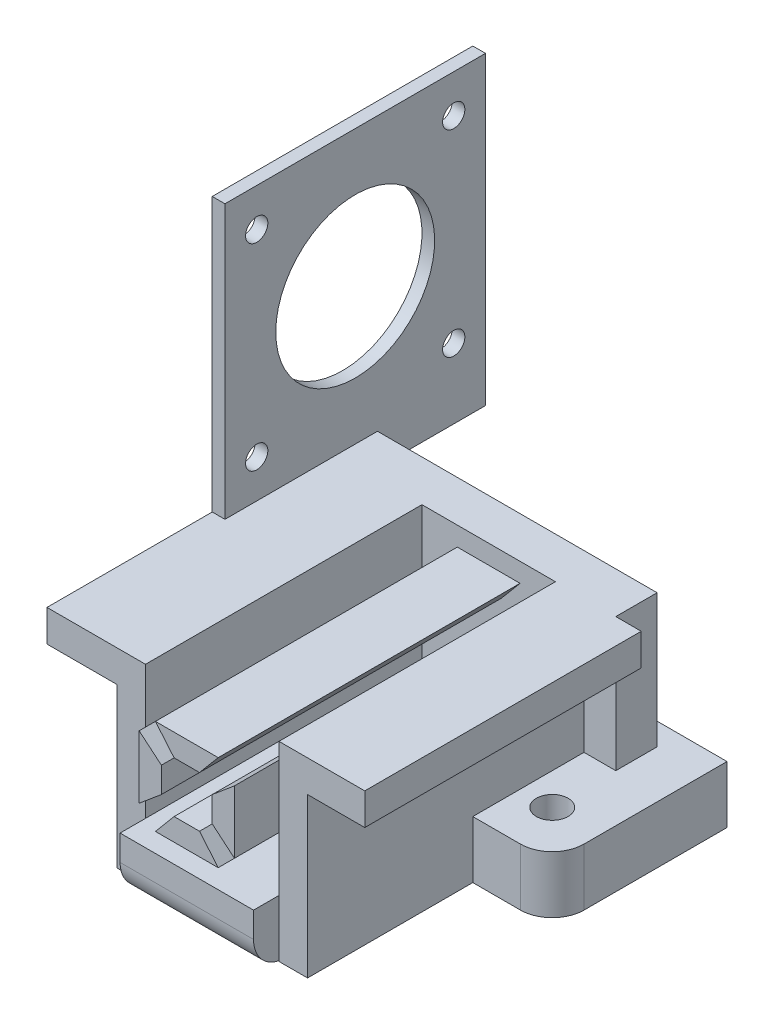
SolidWorks part; units mm, degrees
ref_plane "Front Plane" through (0, 0, 0) normal (0, 0, 1) x (1, 0, 0)
ref_plane "Top Plane" through (0, 0, 0) normal (0, 1, 0) x (1, 0, 0)
ref_plane "Right Plane" through (0, 0, 0) normal (1, 0, 0) x (0, 0, -1)
sketch "Sketch1" plane through (0, 0, 0) normal (0, 1, 0) x (1, 0, 0)
  line L0 (27.5, 55) -> (27.5, 0) construction
  line L1 (5, 0) -> (50, 0)
  line L2 (0, 5) -> (0, 50)
  line L3 (5, 55) -> (50, 55)
  line L4 (55, 5) -> (55, 50)
  line L5 (0, 55) -> (7.5, 55) construction
  line L6 (0, 55) -> (0, 47.5) construction
  line L7 (0, 47.5) -> (7.5, 47.5) construction
  line L8 (7.5, 55) -> (7.5, 47.5) construction
  line L9 (0, 27.5) -> (55, 27.5) construction
  circle A0 centre (7.5, 47.5) radius 2.5
  circle A1 centre (47.5, 47.5) radius 2.5
  circle A2 centre (47.5, 7.5) radius 2.5
  circle A3 centre (7.5, 7.5) radius 2.5
  arc A4 (50, 0) -> (55, 5) centre (50, 5) ccw
  arc A5 (50, 55) -> (55, 50) centre (50, 50) cw
  arc A6 (0, 50) -> (5, 55) centre (5, 50) cw
  arc A7 (5, 0) -> (0, 5) centre (5, 5) cw
  point P23 (55, 55)
  point P29 (0, 0)
  dimension "D3" = 2
  dimension "D5" = 5
  dimension "D1" = 55
  dimension "D2" = 55
  dimension "D4" = 2
extrude "Boss-Extrude2" add sketch "Sketch1" along normal blind 8 and the other way blind 1
sketch "Sketch2" plane through (0, 8, 0) normal (0, 1, 0) x (1, 0, 0)
  line L0 (0, 27.5) -> (55, 27.5)
  line L1 (0, 50) -> (0, 5) construction
  line L2 (55, 5) -> (55, 50) construction
  line L4 (0, 27.5) -> (55, 27.5)
  line L5 (0, 27.5) -> (0, 55)
  line L6 (0, 55) -> (55, 55)
  line L7 (55, 27.5) -> (55, 55)
  circle M3 centre (7.5, 47.5) radius 2.5
  line M5 (55, 5) -> (55, 50)
  arc M6 (55, 50) -> (50, 55) centre (50, 50) ccw
  line M7 (50, 55) -> (5, 55)
  arc M8 (5, 55) -> (0, 50) centre (5, 50) ccw
  line M9 (0, 50) -> (0, 5)
  circle M12 centre (47.5, 47.5) radius 2.5
  dimension "D1" = 27.5
extrude "Cut-Extrude1" cut sketch "Sketch2" against normal through all both and the other way through all contours L0 M9 M5 M6 M7 M8 M12 M3
sketch "Sketch3" plane through (0, 0, -27.5) normal (0, 0, -1) x (-1, 0, 0)
  line L0 (0, -1) -> (0, 8) construction
  line L1 (-55, -1) -> (-37.5, -1) construction
  line L2 (-55, -1) -> (-55, 3.5) construction
  line L3 (-55, 3.5) -> (-37.5, 3.5) construction
  line L4 (-37.5, -1) -> (-37.5, 3.5) construction
  line L5 (0, -1) -> (-55, -1) construction
  circle A0 centre (-37.5, 3.5) radius 3.25
  circle A1 centre (-17.5, 3.5) radius 3.25
  point P10 (0, 3.5)
  dimension "D3" = 6.5
  dimension "D4" = 2
  dimension "D5" = 17.5
  dimension "D1" = 4.5
  dimension "D2" = 17.5
  dimension "D6" = 4.5
sketch3d "3DSketch1"
  point P0 (9.6264, 4.1069, -27.5)
sketch "Sketch5" plane through (0, 8, 0) normal (0, 1, 0) x (1, 0, 0)
  line L0 (27.5, 27.5) -> (27.5, 0)
  line L1 (0, 27.5) -> (55, 27.5) construction
  line L2 (5, 0) -> (50, 0) construction
  line L3 (27.5, 27.5) -> (27.5, 24)
  line L5 (27.5, 24) -> (23, 24)
  line L6 (27.5, 24) -> (27.5, 17.5)
  line L7 (27.5, 17.5) -> (23, 17.5)
  line L8 (23, 24) -> (23, 17.5)
  line L9 (27.5, 24) -> (32, 24)
  line L10 (27.5, 24) -> (27.5, 17.5)
  line L11 (27.5, 17.5) -> (32, 17.5)
  line L12 (32, 24) -> (32, 17.5)
  dimension "D1" = 3.5
  dimension "D2" = 6.5
  dimension "D3" = 4.5
  dimension "D4" = 4.5
  dimension "D5" = 6.5
extrude "Cut-Extrude5" cut sketch "Sketch3" against normal blind 15 draft 0.057 contours A0 | A1
extrude "Boss-Extrude3" add sketch "Sketch5" along normal blind 14.5 contours L5 L8 L7 L0 | L12 L9 L0 L11
sketch "Sketch6" plane through (0, 0, -24) normal (0, 0, -1) x (-1, 0, 0)
  line L0 (-27.5, 8) -> (-27.5, 17)
  line L1 (-32, 8) -> (-23, 8) construction
  circle A0 centre (-27.5, 17) radius 4
  dimension "D2" = 8
  dimension "D1" = 9
extrude "Cut-Extrude4" cut sketch "Sketch6" against normal blind 1.5
sketch "Sketch11" plane through (0, 0, -24) normal (0, 0, -1) x (-1, 0, 0)
  line L0 (-27.5, 22.5) -> (-25.5, 22.5)
  line L1 (-32.4368, 26) -> (-22.5632, 26)
  line L2 (-32, 22.5) -> (-23, 22.5) construction
  line L3 (-25.5, 22.5) -> (-27.5, 22.5)
  line L4 (-25.5, 22.5) -> (-29.5, 22.5)
  line L5 (-25.5, 22.5) -> (-25.5, 26)
  line L6 (-25.5, 26) -> (-29.5, 26)
  line L7 (-29.5, 22.5) -> (-29.5, 26)
  line L8 (-22.5632, 26) -> (-25.5, 22.5)
  line L9 (-29.5, 22.5) -> (-32.4368, 26)
  point P10 (-27.5, 26)
  line M9 (-23, 22.5) -> (-32, 22.5)
  dimension "D1" = 2
  dimension "D2" = 4
  dimension "D3" = 3.5
  dimension "D4" = 40
sketch "Sketch12" plane through (0, 8, 0) normal (0, 1, 0) x (1, 0, 0)
  line L0 (27.5, 17.5) -> (27.5, 0)
  line L1 (32, 17.5) -> (23, 17.5) construction
  line L2 (5, 0) -> (50, 0) construction
  line L3 (17, 0) -> (17, -30)
  line L4 (17, 0) -> (38, 0)
  line L5 (27.5, 0) -> (27.5, -30)
  line L6 (17, -30) -> (38, -30)
  line L7 (38, 0) -> (38, -30)
  point P9 (23.9675, 0)
  line M9 (5, 0) -> (50, 0)
  dimension "D1" = 30
  dimension "D2" = 10.5
extrude "Boss-Extrude7" add sketch "Sketch12" against normal blind 9 contours L7 L5 L6 M9 | L3 L6 L5 M9
sketch "Sketch15" plane through (0, 22.5, 0) normal (0, 1, 0) x (1, 0, 0)
  line L0 (32, 24) -> (32, 17.5) construction
  line L1 (32, 17.5) -> (23, 17.5)
  line L2 (32, 17.5) -> (32, 24)
  line L3 (32, 24) -> (23, 24)
  line L4 (23, 17.5) -> (23, 24)
  line L5 (32, 17.5) -> (23, 17.5) construction
extrude "Boss-Extrude8" add sketch "Sketch15" along normal blind 3.5
extrude "Boss-Extrude9" add sketch "Sketch11" against normal blind 54 contours L9 L7 L1 | L7 L5 L1 M9 | L8 L1 L5
fillet "Fillet4" radius 5 1 edges at (27.5, -1, 30)
sketch "Sketch18" plane through (0, 26, 0) normal (0, 1, 0) x (1, 0, 0)
  line L0 (32.4368, -30) -> (32.4368, 24) construction
  line L1 (22.5632, 24) -> (32.4368, 24)
  line L2 (22.5632, 24) -> (22.5632, 17.5)
  line L3 (22.5632, 17.5) -> (32.4368, 17.5)
  line L4 (32.4368, 24) -> (32.4368, 17.5)
  dimension "D1" = 6.5
extrude "Boss-Extrude11" add sketch "Sketch18" along normal blind 0.5
sketch "Sketch20" plane through (0, 8, 0) normal (0, 1, 0) x (1, 0, 0)
  line L0 (27.5, -1030) -> (27.5, 48970) construction
  line L1 (17, -30) -> (38, -30) construction
  line L2 (32, 17.5) -> (23, 17.5) construction
  line L3 (27.5, 17.5) -> (16.5, 17.5)
  line L4 (27.5, 17.5) -> (27.5, 0)
  line L5 (27.5, 0) -> (16.5, 0)
  line L6 (16.5, 17.5) -> (16.5, 0)
  line L7 (27.5, 17.5) -> (16.5, 0) construction
  line L8 (27.5, 0) -> (16.5, 17.5) construction
  line L10 (27.5, 17.5) -> (38.5, 17.5)
  line L11 (27.5, 17.5) -> (27.5, 0)
  line L12 (27.5, 0) -> (38.5, 0)
  line L13 (38.5, 17.5) -> (38.5, 0)
  line L14 (27.5, 17.5) -> (38.5, 0) construction
  line L15 (27.5, 0) -> (38.5, 17.5) construction
  line L16 (38.5, 17.5) -> (42.5, 17.5)
  line L17 (38.5, 17.5) -> (38.5, 0)
  line L18 (38.5, 0) -> (42.5, 0)
  line L19 (42.5, 17.5) -> (42.5, 0)
  line L21 (16.5, 17.5) -> (12.5, 17.5)
  line L22 (16.5, 17.5) -> (16.5, 0)
  line L23 (16.5, 0) -> (12.5, 0)
  line L24 (12.5, 17.5) -> (12.5, 0)
  line L26 (42.5, 0) -> (38.5, 0)
  line L27 (42.5, 0) -> (42.5, 17.5)
  line L28 (42.5, 17.5) -> (38.5, 17.5)
  line L29 (38.5, 0) -> (38.5, 17.5)
  line L30 (16.5, 0) -> (12.5, 0)
  line L31 (16.5, 0) -> (16.5, 17.5)
  line L32 (16.5, 17.5) -> (12.5, 17.5)
  line L33 (12.5, 0) -> (12.5, 17.5)
  point P5 (27.5, -30)
  point P9 (22, 8.75)
  point P14 (33, 8.75)
  line M12 (5, 0) -> (17, 0)
  line M16 (38, 0) -> (50, 0)
  dimension "D2" = 11
  dimension "D3" = 17.5
  dimension "D4" = 4
extrude "Boss-Extrude12" add sketch "Sketch20" along normal blind 18 contours L21 L24 L6 M12 | L19 L16 L13 M16
sketch "Sketch21" plane through (12.5, 0, 0) normal (-1, 0, 0) x (0, 0, 1)
  line L0 (-17.5, 26) -> (-17.5, 8) construction
  line L1 (0, 26) -> (-17.5, 26)
  line L2 (0, 26) -> (0, 24)
  line L3 (0, 24) -> (-17.5, 24)
  line L4 (-17.5, 26) -> (-17.5, 24)
  dimension "D1" = 2
sketch "Sketch22" plane through (12.5, 0, 0) normal (-1, 0, 0) x (0, 0, 1)
  line L1 (-17.5, 24) -> (0, 24)
  line L2 (-17.5, 24) -> (-17.5, 28)
  line L3 (-17.5, 28) -> (0, 28)
  line L4 (0, 24) -> (0, 28)
  dimension "D1" = 4
extrude "Boss-Extrude13" add sketch "Sketch22" along normal blind 11 and the other way blind 4 contours L3 L4 L1 L2
sketch "Sketch25" plane through (0, 28, 0) normal (0, 1, 0) x (1, 0, 0)
  line L2 (1.5, 17.5) -> (16.5, 17.5) construction
  line L3 (1.5, 0) -> (3.5, 0)
  line L4 (1.5, 0) -> (1.5, 17.5)
  line L5 (1.5, 17.5) -> (3.5, 17.5)
  line L6 (3.5, 0) -> (3.5, 17.5)
  dimension "D1" = 2
extrude "Boss-Extrude14" add sketch "Sketch25" along normal blind 41
sketch "Sketch28" plane through (1.5, 0, 0) normal (-1, 0, 0) x (0, 0, 1)
  line L2 (0, 69) -> (-41, 69)
  line L3 (0, 69) -> (0, 24)
  line L4 (0, 24) -> (-41, 24)
  line L5 (-41, 69) -> (-41, 24)
  dimension "D1" = 45
  dimension "D2" = 41
extrude "Boss-Extrude15" add sketch "Sketch28" against normal blind 2
sketch "Sketch29" plane through (1.5, 0, 0) normal (-1, 0, 0) x (0, 0, 1)
  line L1 (0, 24) -> (-5, 24)
  line L2 (0, 24) -> (0, 35)
  line L3 (0, 35) -> (-5, 35)
  line L4 (-5, 24) -> (-5, 35)
  circle A0 centre (-5, 35) radius 1.75
  circle A1 centre (-36, 35) radius 1.75
  circle A2 centre (-36, 66) radius 1.75
  circle A3 centre (-5, 66) radius 1.75
  dimension "D6" = 31
  dimension "D1" = 11
  dimension "D2" = 5
  dimension "D7" = 31
  dimension "D4" = 2
  dimension "D5" = 2
extrude "Cut-Extrude8" cut sketch "Sketch29" against normal blind 9 contours A1 | A3 | A0 | A2
sketch "Sketch30" plane through (42.5, 0, 0) normal (1, 0, 0) x (0, 0, -1)
  line L0 (17.5, 26) -> (17.5, 8) construction
  line L1 (0, 26) -> (17.5, 26)
  line L2 (0, 26) -> (0, 24)
  line L3 (0, 24) -> (17.5, 24)
  line L4 (17.5, 26) -> (17.5, 24)
  line L6 (0, 24) -> (17.5, 24)
  line L7 (0, 24) -> (0, 28)
  line L8 (0, 28) -> (17.5, 28)
  line L9 (17.5, 24) -> (17.5, 28)
  line M4 (17.5, 8) -> (17.5, 26)
  line M5 (17.5, 26) -> (0, 26)
  line M6 (0, 26) -> (0, 8)
  dimension "D1" = 2
  dimension "D2" = 4
extrude "Boss-Extrude16" add sketch "Sketch30" along normal blind 9 and the other way blind 4 contours L3 M6 M4 M5 | L9 L8 L7 M5
sketch "Sketch31" plane through (3.5, 0, 0) normal (1, 0, 0) x (0, 0, -1)
  line L1 (41, 69) -> (20.5, 69)
  line L2 (41, 69) -> (41, 47)
  line L3 (41, 47) -> (20.5, 47)
  line L4 (20.5, 69) -> (20.5, 47)
  circle A0 centre (20.5, 47) radius 10
  dimension "D3" = 20
  dimension "D1" = 22
  dimension "D2" = 20.5
extrude "Cut-Extrude9" cut sketch "Sketch31" against normal blind 9 contours L4 A0 L3 | L3 A0 L4
sketch "Sketch32" plane through (0, 0, -17.5) normal (0, 0, -1) x (-1, 0, 0)
  line L1 (-16.5, 28) -> (-3.5, 28)
  line L2 (-16.5, 28) -> (-16.5, 24)
  line L3 (-16.5, 24) -> (-3.5, 24)
  line L4 (-3.5, 28) -> (-3.5, 24)
extrude "Boss-Extrude17" add sketch "Sketch32" along normal blind 23.5
sketch "Sketch33" plane through (0, 8, 0) normal (0, 1, 0) x (1, 0, 0)
  line L0 (38.5, 17.5) -> (38.5, 0)
  line L1 (38.5, 17.5) -> (38, 17.5)
  line L2 (38.5, 0) -> (38, 0)
  line L3 (38, 17.5) -> (38, 0)
  line L4 (16.5, 17.5) -> (16.5, 0)
  line L5 (16.5, 17.5) -> (17, 17.5)
  line L6 (16.5, 0) -> (17, 0)
  line L7 (17, 17.5) -> (17, 0)
  dimension "D1" = 0.5
  dimension "D2" = 0.5
extrude "Boss-Extrude18" add sketch "Sketch33" along normal blind 20
sketch "Sketch34" plane through (0, 0, 0) normal (0, 0, 1) x (1, 0, 0)
  line L0 (42.5, 24) -> (42.5, 8) construction
  line L1 (51.5, 28) -> (42.5, 28)
  line L2 (51.5, 28) -> (51.5, 24)
  line L3 (51.5, 24) -> (42.5, 24)
  line L4 (42.5, 28) -> (42.5, 24)
  line L5 (42.5, 24) -> (51.5, 24) construction
  line L7 (42.5, 28) -> (38, 28)
  line L8 (42.5, 28) -> (42.5, -1)
  line L9 (42.5, -1) -> (38, -1)
  line L10 (38, 28) -> (38, -1)
  line L11 (17, 28) -> (1.5, 28)
  line L12 (17, 28) -> (17, 24)
  line L13 (17, 24) -> (1.5, 24)
  line L14 (1.5, 28) -> (1.5, 24)
  line L15 (12.5, 24) -> (17, 24)
  line L16 (12.5, 24) -> (12.5, -1)
  line L17 (12.5, -1) -> (17, -1)
  line L18 (17, 24) -> (17, -1)
  line M1 (42.5, 8) -> (42.5, 24)
  line M2 (42.5, 24) -> (51.5, 24)
  line M3 (51.5, 24) -> (51.5, 28)
  line M4 (51.5, 28) -> (38, 28)
  line M5 (38, 28) -> (38, 8)
  line M6 (38, 8) -> (38, -1)
  line M7 (38, -1) -> (50, -1)
extrude "Boss-Extrude19" add sketch "Sketch34" along normal blind 26 contours L18 L13 L16 L17 | L11 L14 L13 L12 | L8 L4 M1 M4 M5 M6 M7 | L4 M4 M2 M3
sketch "Sketch35" plane through (0, 0, -17.5) normal (0, 0, 1) x (1, 0, 0)
  line L1 (32.4368, 26.5) -> (22.5632, 26.5)
  line L2 (32.4368, 26.5) -> (32.4368, 26)
  line L3 (32.4368, 26) -> (22.5632, 26)
  line L4 (22.5632, 26.5) -> (22.5632, 26)
extrude "Boss-Extrude20" add sketch "Sketch35" along normal blind 47.5
sketch "Sketch37" plane through (0, 0, -17.5) normal (0, 0, 1) x (1, 0, 0)
  line L0 (27.5, 8) -> (29.5, 8)
  line L2 (32, 8) -> (23, 8) construction
  line L3 (29.5, 12) -> (33.1362, 7.6666)
  line L4 (29.5, 8) -> (25.5, 8)
  line L5 (29.5, 8) -> (29.5, 12)
  line L6 (29.5, 12) -> (25.5, 12)
  line L7 (25.5, 8) -> (25.5, 12)
  line L8 (25.5, 12) -> (21.8638, 7.6666)
  line L9 (21.8638, 7.6666) -> (33.1362, 7.6666)
  line M8 (32, 8) -> (32, 25.4794)
  line M12 (23, 25.4794) -> (23, 8)
  line M13 (23, 8) -> (32, 8)
  dimension "D1" = 2
  dimension "D2" = 4
  dimension "D3" = 4
  dimension "D4" = 40
  dimension "D5" = 40
extrude "Boss-Extrude21" add sketch "Sketch37" along normal blind 47.5 contours L7 L8 M12 M13 | L7 L5 L6 M13 | L5 L3 M13 M8 | L8 L9 L3 M8 M13 M12
sketch "Sketch38" plane through (0, 0, 30) normal (0, 0, 1) x (1, 0, 0)
  line L1 (22.5632, 26.5) -> (22.1436, 26.5)
  line L2 (22.5632, 26.5) -> (22.5632, 8)
  line L3 (22.5632, 8) -> (22.1436, 8)
  line L4 (22.1436, 26.5) -> (22.1436, 8)
  line L5 (32.4368, 26.5) -> (32.8564, 26.5)
  line L6 (32.4368, 26.5) -> (32.4368, 8)
  line L7 (32.4368, 8) -> (32.8564, 8)
  line L8 (32.8564, 26.5) -> (32.8564, 8)
extrude "Cut-Extrude10" cut sketch "Sketch38" against normal blind 90.5
ref_plane "Plane1" through (5, 8, 0) normal (0, 1, 0) x (1, 0, 0)
sketch "Sketch45" plane through (0, 8, 0) normal (0, 1, 0) x (1, 0, 0)
  line L0 (0, 15.4413) -> (0, -89.262) construction
  line L1 (-11, 15.4413) -> (-11, -89.262)
  dimension "D1" = 11
sketch "Sketch46" plane through (0, 0, 0) normal (-1, 0, 0) x (0, 0, 1)
  line L1 (-27.5, -1) -> (-5, -1)
  line L2 (-27.5, -1) -> (-27.5, 8)
  line L3 (-27.5, 8) -> (-5, 8)
  line L4 (-5, -1) -> (-5, 8)
  line L5 (-27.5, 8) -> (0, 8)
  line L6 (-27.5, 8) -> (-27.5, -1)
  line L7 (-27.5, -1) -> (0, -1)
  line L8 (0, 8) -> (0, -1)
  line M2 (-27.5, 8) -> (-27.5, -1)
  line M3 (-27.5, -1) -> (-5, -1)
  line M4 (-5, -1) -> (-5, 8)
  line M5 (-5, 8) -> (-27.5, 8)
  dimension "D1" = 27.5
extrude "Boss-Extrude26" add sketch "Sketch46" against normal blind 11.5 contours M5 M2 M3 M4 | L8 L5 L7 M4
sketch "Sketch47" plane through (0, 0, 0) normal (-1, 0, 0) x (0, 0, 1)
  line L1 (-27.5, 8) -> (0, 8)
  line L2 (-27.5, 8) -> (-27.5, -1)
  line L3 (-27.5, -1) -> (0, -1)
  line L4 (0, 8) -> (0, -1)
extrude "Boss-Extrude27" add sketch "Sketch47" along normal blind 11
sketch "Sketch48" plane through (0, 8, 0) normal (0, 1, 0) x (1, 0, 0)
  line L0 (12.5, 17.5) -> (12.5, 24)
  line L1 (23, 24) -> (12.5, 24)
  line L2 (23, 24) -> (23, 17.5)
  line L3 (23, 17.5) -> (12.5, 17.5)
  line L4 (12.5, 24) -> (12.5, 17.5)
  line L5 (12.5, 17.5) -> (7.5, 17.5)
  line L6 (12.5, 24) -> (7.5, 24)
  line L7 (7.5, 17.5) -> (7.5, 24)
  line L8 (42.5, 24) -> (42.5, 17.5)
  line L9 (32, 24) -> (42.5, 24)
  line L10 (32, 24) -> (32, 17.5)
  line L11 (32, 17.5) -> (42.5, 17.5)
  line L12 (42.5, 24) -> (42.5, 17.5)
  line L13 (42.5, 24) -> (47.5, 24)
  line L14 (42.5, 17.5) -> (47.5, 17.5)
  line L15 (47.5, 24) -> (47.5, 17.5)
  line M3 (12.5, 17.5) -> (17, 17.5)
  line M8 (22.5632, 17.5) -> (23, 17.5)
  line M9 (23, 17.5) -> (23, 24)
  line M11 (32, 24) -> (32, 17.5)
  line M12 (32, 17.5) -> (32.4368, 17.5)
  line M17 (38, 17.5) -> (42.5, 17.5)
  dimension "D1" = 5
  dimension "D2" = 5
sketch "Sketch49" plane through (0, 0, -24) normal (0, 0, -1) x (-1, 0, 0)
  line L0 (-17.5, 3.5) -> (-27.5, 17)
  line L1 (-27.5, 17) -> (-17.5, 17)
  line L2 (-17.5, 17) -> (-17.5, 3.5)
  line L3 (-27.5, 17) -> (-37.5, 3.5)
  line L4 (-37.5, 3.5) -> (-37.5, 17)
  line L5 (-37.5, 17) -> (-27.5, 17)
  circle A0 centre (-37.5, 17) radius 4
  circle A1 centre (-17.5, 17) radius 4
  dimension "D1" = 8
  dimension "D2" = 8
extrude "Boss-Extrude31" add sketch "Sketch48" along normal blind 18.5 contours L11 L8 L9 M12 M17 M11 | L15 L13 L8 L14 | L3 L1 L0 M8 M9 M3 | L7 L5 L0 L6
sketch "Sketch50" plane through (0, 0, -24) normal (0, 0, -1) x (-1, 0, 0)
  circle A0 centre (-17.5, 17) radius 4
  circle A1 centre (-37.5, 17) radius 4
  dimension "D1" = 8
  dimension "D2" = 8
extrude "Cut-Extrude11" cut sketch "Sketch50" against normal blind 1.5
sketch "Sketch51" plane through (0, 0, -24) normal (0, 0, -1) x (-1, 0, 0)
  line L1 (-32.4593, 12.5515) -> (-22.8331, 12.5515)
  line L2 (-32.4593, 12.5515) -> (-32.4593, 21.6767)
  line L3 (-32.4593, 21.6767) -> (-22.8331, 21.6767)
  line L4 (-22.8331, 12.5515) -> (-22.8331, 21.6767)
extrude "Boss-Extrude32" add sketch "Sketch51" against normal blind 1.5
sketch "Sketch53" plane through (0, 0, -24) normal (0, 0, -1) x (-1, 0, 0)
  line L0 (-27.5, 17) -> (-27.5, 8)
  line L1 (-47.5, 8) -> (-7.5, 8) construction
  line L2 (-27.5, 8) -> (-27.5, 26.5)
  line L3 (-47.5, 26.5) -> (-16.5, 26.5) construction
  line L4 (-27.5, 17.25) -> (-23.5, 17.25)
  line L5 (-23.5, 17.25) -> (-31.5, 17.25)
  line L7 (-31.5, 13.25) -> (-23.5, 13.25)
  line L8 (-31.5, 13.25) -> (-31.5, 21.25)
  line L9 (-31.5, 21.25) -> (-23.5, 21.25)
  line L10 (-23.5, 13.25) -> (-23.5, 21.25)
  line L11 (-31.5, 13.25) -> (-23.5, 21.25) construction
  line L12 (-31.5, 21.25) -> (-23.5, 13.25) construction
  dimension "D1" = 4
  dimension "D2" = 4
  dimension "D3" = 8
  dimension "D4" = 8
sketch "Sketch54" plane through (0, 0, -17.5) normal (0, 0, 1) x (1, 0, 0)
  line L0 (27.5, 22.5) -> (27.5, 14.5)
  line L1 (29.5, 22.5) -> (25.5, 22.5) construction
  line L3 (23.5, 22.5) -> (31.5, 22.5)
  line L4 (23.5, 22.5) -> (23.5, 14.5)
  line L5 (23.5, 14.5) -> (31.5, 14.5)
  line L6 (31.5, 22.5) -> (31.5, 14.5)
  line L7 (23.5, 22.5) -> (31.5, 14.5) construction
  line L8 (23.5, 14.5) -> (31.5, 22.5) construction
  point P4 (27.5, 18.5)
  line M17 (29.5, 22.5) -> (25.5, 22.5)
  dimension "D1" = 8
  dimension "D2" = 8
  dimension "D3" = 8
extrude "Boss-Extrude35" add sketch "Sketch54" along normal blind 47.5 contours L6 L3 L0 L5 M17 | L4 L5 L0 L3 M17
sketch "Sketch55" plane through (0, 0, 30) normal (0, 0, 1) x (1, 0, 0)
  line L1 (32.4368, 26.5) -> (22.5632, 26.5)
  line L2 (32.4368, 26.5) -> (32.4368, 26)
  line L3 (32.4368, 26) -> (22.5632, 26)
  line L4 (22.5632, 26.5) -> (22.5632, 26)
extrude "Cut-Extrude12" cut sketch "Sketch55" against normal blind 47.5
sketch "Sketch57" plane through (0, 0, 30) normal (0, 0, 1) x (1, 0, 0)
  line L0 (31.5, 20.5) -> (31.5, 16.5)
  line L1 (35, 18.4644) -> (35, 13.5632)
  line L2 (25.5, 22.5) -> (29.5, 22.5)
  line L3 (29.5, 22.5) -> (32.4368, 26)
  line L4 (29.5, 22.5) -> (29.5, 26)
  line L5 (22.5632, 26) -> (32.4368, 26) construction
  line L6 (31.5, 22.5) -> (31.5, 14.5) construction
  line L7 (35, 13.5632) -> (31.5, 16.5)
  line L8 (31.5, 16.5) -> (35, 16.5)
  line L9 (31.5, 16.5) -> (31.5, 20.4288)
  line L10 (31.5, 20.4288) -> (35, 20.4288)
  line L11 (35, 16.5) -> (35, 20.4288)
  line L12 (35, 18.5356) -> (35, 23.4368)
  line L13 (35, 16.5) -> (31.5, 16.5)
  line L14 (35, 16.5) -> (35, 18.5)
  line L15 (35, 18.5) -> (31.5, 18.5)
  line L16 (31.5, 16.5) -> (31.5, 18.5)
  line L17 (35, 23.4368) -> (31.5, 20.5)
  line L18 (27.5, 22.5) -> (27.5, 14.5) construction
  line L19 (23.5, 14.5) -> (31.5, 14.5) construction
  line L20 (20, 13.5632) -> (23.5, 16.5)
  line L21 (23.5, 16.5) -> (20, 16.5)
  line L22 (20, 18.4644) -> (20, 13.5632)
  line L23 (20, 18.5356) -> (20, 23.4368)
  line L24 (20, 23.4368) -> (23.5, 20.5)
  line L25 (23.5, 20.5) -> (23.5, 16.5)
  line L26 (27.5, 18.5) -> (31.5, 18.5) construction
  line L27 (31.5, 18.5) -> (23.5, 18.5) construction
  line L28 (23.5, 20.5) -> (23.5, 16.5)
  line L29 (32.4368, 26) -> (22.5632, 26)
  line L30 (22.5632, 26) -> (25.5, 22.5)
  line L31 (25.5, 14.5) -> (29.5, 14.5)
  line L32 (22.5632, 11) -> (25.5, 14.5)
  line L33 (32.4368, 11) -> (22.5632, 11)
  line L34 (29.5, 14.5) -> (32.4368, 11)
  line L35 (23.5, 16.5) -> (20, 13.5632)
  line L36 (20, 13.5632) -> (20, 23.4368)
  line L37 (20, 23.4368) -> (23.5, 20.5)
  line L38 (23.5, 18.5) -> (23.5, 20.5)
  line M12 (23.5, 22.5) -> (23.5, 14.5)
  line M13 (23.5, 14.5) -> (31.5, 14.5)
  line M14 (31.5, 14.5) -> (31.5, 22.5)
  dimension "D1" = 2
  dimension "D2" = 3.5
  dimension "D3" = 130
extrude "Boss-Extrude37" add sketch "Sketch57" against normal blind 47.5 contours L12 L17 L0 L10 | L15 L11 L10 L9 | L11 L15 L8 L1 M14 | L8 L7 L1 | L34 L32 L33 M13 | L36 L22 L21 L28 L24 L23 M12 | L21 L22 L20
sketch "Sketch61" plane through (0, 0, 30) normal (0, 0, 1) x (1, 0, 0)
  line L0 (32.4368, 8) -> (22.5632, 8)
  line L1 (22.5632, 8) -> (22.5632, 8.5)
  line L2 (22.5632, 8.5) -> (24.6609, 11)
  line L3 (24.6609, 11) -> (30.3391, 11)
  line L4 (30.3391, 11) -> (32.4368, 8.5)
  line L5 (32.4368, 8.5) -> (32.4368, 8)
extrude "Cut-Extrude17" cut sketch "Sketch61" against normal blind 47.5
sketch "Sketch62" plane through (0, 0, 30) normal (0, 0, 1) x (1, 0, 0)
  line L1 (23.5, 22.5) -> (31.5, 22.5)
  line L2 (23.5, 22.5) -> (23.5, 14.5)
  line L3 (23.5, 14.5) -> (31.5, 14.5)
  line L4 (31.5, 22.5) -> (31.5, 14.5)
extrude "Cut-Extrude18" cut sketch "Sketch62" against normal blind 47.5
sketch "Sketch63" plane through (0, 0, -41) normal (0, 0, -1) x (-1, 0, 0)
  line L1 (-3.5, 28) -> (-16.5, 28)
  line L2 (-3.5, 28) -> (-3.5, 24)
  line L3 (-3.5, 24) -> (-16.5, 24)
  line L4 (-16.5, 28) -> (-16.5, 24)
extrude "Cut-Extrude20" cut sketch "Sketch63" against normal blind 17
sketch "Sketch64" plane through (0, 0, -17.5) normal (0, 0, -1) x (-1, 0, 0)
  line L1 (-17, 26.5) -> (-16.5, 26.5)
  line L2 (-17, 26.5) -> (-17, 28)
  line L3 (-17, 28) -> (-16.5, 28)
  line L4 (-16.5, 26.5) -> (-16.5, 28)
extrude "Boss-Extrude38" add sketch "Sketch64" along normal blind 6.5
sketch "Sketch65" plane through (0, 28, 0) normal (0, 1, 0) x (1, 0, 0)
  line L1 (51.5, 17.5) -> (44.5, 17.5)
  line L2 (51.5, 17.5) -> (51.5, 14.5)
  line L3 (51.5, 14.5) -> (44.5, 14.5)
  line L4 (44.5, 17.5) -> (44.5, 14.5)
  dimension "D1" = 3
  dimension "D2" = 7
extrude "Cut-Extrude21" cut sketch "Sketch65" against normal blind 1.5
sketch "Sketch66" plane through (1.5, 0, 0) normal (-1, 0, 0) x (0, 0, 1)
  line L0 (-10.5, 47) -> (-30.5, 47)
  line L2 (-31.5643, 36.4388) -> (-9.4357, 36.4388)
  line L3 (-31.5643, 36.4388) -> (-31.5643, 57.5612)
  line L4 (-31.5643, 57.5612) -> (-9.4357, 57.5612)
  line L5 (-9.4357, 36.4388) -> (-9.4357, 57.5612)
  line L6 (-31.5643, 36.4388) -> (-9.4357, 57.5612) construction
  line L7 (-31.5643, 57.5612) -> (-9.4357, 36.4388) construction
  circle A0 centre (-20.5, 47) radius 10 construction
  point P5 (-20.5, 47)
  circle M1 centre (-20.5, 47) radius 10
extrude "Boss-Extrude39" add sketch "Sketch66" against normal blind 2 contours L0 M1 | L0 M1
sketch "Sketch67" plane through (1.5, 0, 0) normal (-1, 0, 0) x (0, 0, 1)
  line L0 (0, 28) -> (-41, 28)
  line L1 (-41, 69) -> (-41, 24) construction
  line L2 (-41, 28) -> (-20.5, 28)
  line L3 (-20.5, 28) -> (-20.5, 69)
  line L4 (-41, 69) -> (0, 69) construction
  line L5 (-20.5, 69) -> (-20.5, 50.5)
  line L6 (-20.5, 50.5) -> (-41, 50.5)
  line L7 (-41, 50.5) -> (0, 50.5)
  circle A0 centre (-20.5, 50.5) radius 12.5
  dimension "D1" = 25
  dimension "D2" = 22.5
extrude "Cut-Extrude22" cut sketch "Sketch67" against normal blind 155 contours L7 A0 L3 | L3 A0 L7 | L6 A0 L3 | L3 A0 L6
sketch "Sketch69" plane through (0, 26.5, 0) normal (0, 1, 0) x (1, 0, 0)
  line L0 (44.5, 14.5) -> (51.5, 14.5)
  line L1 (51.5, 14.5) -> (51.5, 17.5)
  line L2 (51.5, 17.5) -> (47.5, 17.5)
  line L3 (47.5, 17.5) -> (47.5, 24)
  line L4 (47.5, 24) -> (17, 24)
  line L5 (17, 24) -> (17, 17.5)
  line L6 (17, 17.5) -> (44.5, 17.5)
  line L7 (44.5, 17.5) -> (44.5, 14.5)
extrude "Boss-Extrude40" add sketch "Sketch69" along normal blind 1.5
sketch "Sketch70" plane through (0, 69, 0) normal (0, 1, 0) x (1, 0, 0)
  line L0 (1.5, 0) -> (3.5, 0) construction
  line L1 (3.5, 41) -> (1.5, 41)
  line L2 (3.5, 41) -> (3.5, 0)
  line L3 (3.5, 0) -> (1.5, 0)
  line L4 (1.5, 41) -> (1.5, 0)
  line L5 (1.5, 41) -> (1.5, 0) construction
sketch "Sketch71" plane through (0, 0, -17.5) normal (0, 0, 1) x (1, 0, 0)
  line L0 (32.4368, 26) -> (22.5632, 26)
  line L1 (22.5632, 26) -> (25.5, 22.5)
  line L2 (25.5, 22.5) -> (29.5, 22.5)
  line L3 (29.5, 22.5) -> (32.4368, 26)
  line L4 (35, 23.4368) -> (31.5, 20.5)
  line L5 (31.5, 20.5) -> (31.5, 16.5)
  line L6 (31.5, 16.5) -> (35, 13.5632)
  line L7 (35, 13.5632) -> (35, 23.4368)
  line L8 (20, 23.4368) -> (20, 13.5632)
  line L10 (20, 13.5632) -> (20, 23.4368) construction
  line L11 (20, 13.5632) -> (23.5, 16.5)
  line L12 (23.5, 16.5) -> (23.5, 20.5)
  line L13 (23.5, 20.5) -> (20, 23.4368)
  line L14 (25.5, 14.5) -> (29.5, 14.5)
  line L15 (29.5, 14.5) -> (32.4368, 11)
  line L16 (32.4368, 11) -> (22.5632, 11)
  line L17 (22.5632, 11) -> (25.5, 14.5)
extrude "Boss-Extrude41" add sketch "Sketch70" along normal blind 3
sketch "Sketch72" plane through (0, 28, 0) normal (0, 1, 0) x (1, 0, 0)
  line L0 (17, -26) -> (1.5, -26)
  line L1 (17, -26) -> (17, 17.5)
  line L2 (17, 17.5) -> (38, 17.5)
  line L3 (38, 17.5) -> (38, -26) construction
  line L4 (38, 17.5) -> (38, -26) construction
  line L5 (38, 17.5) -> (38, -26)
  line L6 (38, -26) -> (51.5, -26)
  line L7 (51.5, -26) -> (51.5, 17.5)
  line L8 (51.5, -26) -> (51.5, 17.5) construction
  line L9 (51.5, 17.5) -> (47.5, 17.5)
  line L10 (47.5, 17.5) -> (47.5, 24)
  line L11 (47.5, 24) -> (1.5, 24)
  line L12 (1.5, 41) -> (1.5, 0) construction
  line L13 (1.5, 24) -> (1.5, 0)
  line L14 (1.5, 0) -> (1.5, -26)
extrude "Boss-Extrude42" add sketch "Sketch72" along normal blind 1
